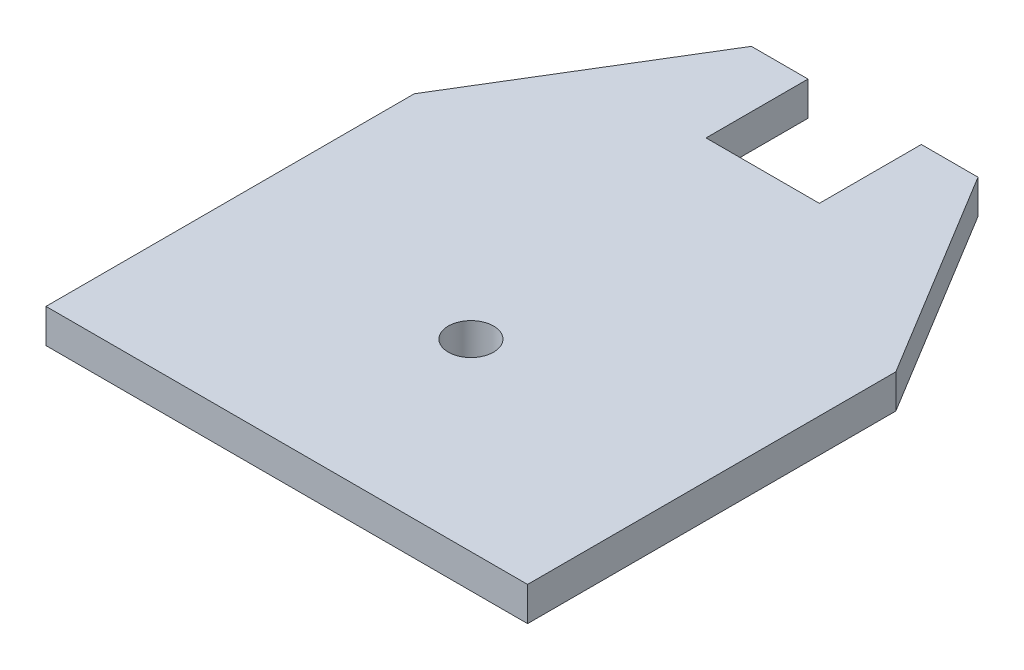
SolidWorks part; units mm, degrees
ref_plane "Спереди" through (0, 0, 0) normal (0, 0, 1) x (1, 0, 0)
ref_plane "Сверху" through (0, 0, 0) normal (0, 1, 0) x (1, 0, 0)
ref_plane "Справа" through (0, 0, 0) normal (1, 0, 0) x (0, 0, -1)
sketch "Эскиз1" plane through (0, 0, 0) normal (0, 1, 0) x (1, 0, 0)
  line L1 (-42.5, 40.665) -> (42.5, 40.665)
  line L2 (-42.5, 40.665) -> (-42.5, -61.335)
  line L3 (-42.5, -61.335) -> (42.5, -61.335)
  line L4 (42.5, 40.665) -> (42.5, -61.335)
extrude "Вытянуть1" add sketch "Эскиз1" along normal blind 6
sketch "Эскиз2" plane through (0, 6, 0) normal (0, 1, 0) x (1, 0, 0)
  line L0 (42.5, 3.665) -> (20, 40.665)
  line L1 (20, 40.665) -> (42.5, 40.665)
  line L2 (42.5, 40.665) -> (42.5, 3.665)
  line L3 (0, 40) -> (0, 67.0971) construction
  line L4 (-42.5, 40.665) -> (-42.5, -61.335) construction
  line L5 (-42.5, 40.665) -> (-42.5, 3.665)
  line L6 (-20, 40.665) -> (-42.5, 40.665)
  line L7 (-42.5, 3.665) -> (-20, 40.665)
extrude "Вырез-Вытянуть1" cut sketch "Эскиз2" against normal through all
sketch "Эскиз3" plane through (0, 6, 0) normal (0, 1, 0) x (1, 0, 0)
  line L0 (-42.5, -1.335) -> (42.5, -1.335) construction
  line L1 (-42.5, -61.335) -> (42.5, -61.335) construction
  circle A0 centre (0, -28.835) radius 4
  dimension "D1" = 32.5
extrude "Вырез-Вытянуть2" cut sketch "Эскиз3" against normal through all
sketch "Эскиз4" plane through (0, 6, 0) normal (0, 1, 0) x (1, 0, 0)
  line L1 (10, 22.665) -> (-10, 22.665)
  line L2 (10, 22.665) -> (10, 40.665)
  line L3 (10, 40.665) -> (-10, 40.665)
  line L4 (-10, 22.665) -> (-10, 40.665)
extrude "Вырез-Вытянуть3" cut sketch "Эскиз4" against normal through all
